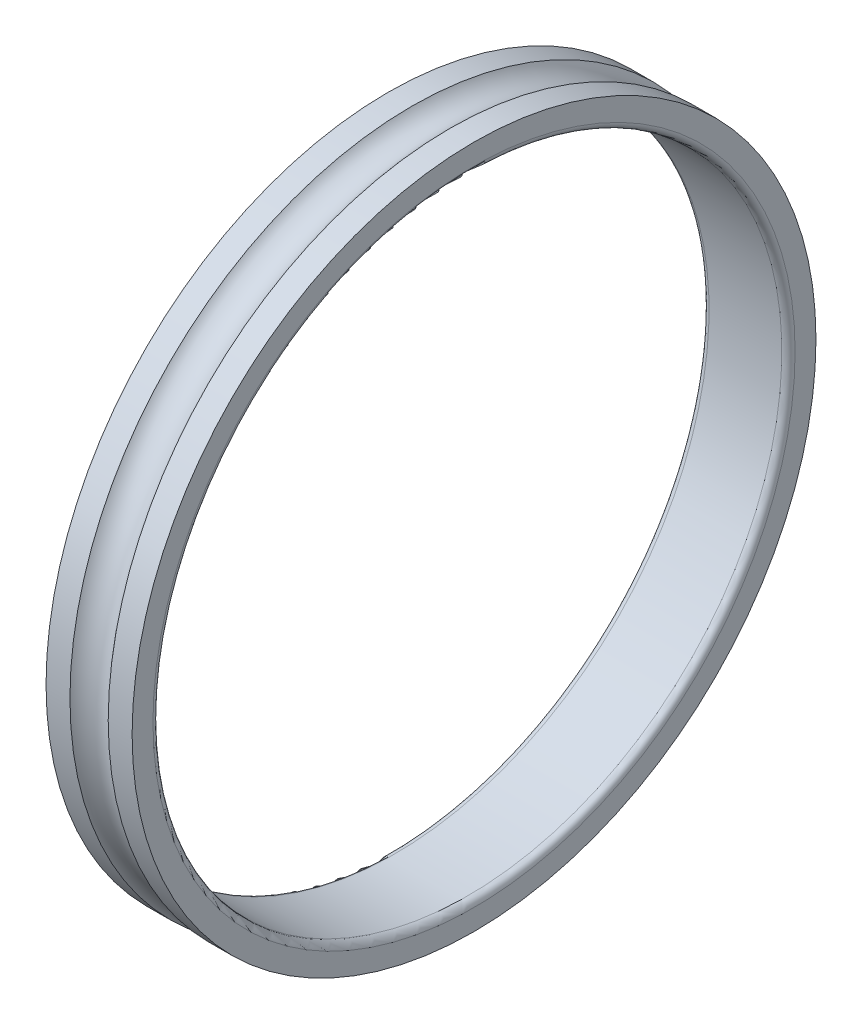
SolidWorks part; units mm, degrees
ref_plane "Piano frontale" through (0, 0, 0) normal (0, 0, 1) x (1, 0, 0)
ref_plane "Piano superiore" through (0, 0, 0) normal (0, 1, 0) x (1, 0, 0)
ref_plane "Piano destro" through (0, 0, 0) normal (1, 0, 0) x (0, 0, -1)
ref_plane "Piano1" through (0, 0, 0) normal (0, 0, 1) x (1, 0, 0)
sketch "Schizzo1" plane through (0, 0, 0) normal (0, 0, 1) x (1, 0, 0)
  line L0 (1, 47.5) -> (12, 47.5)
  line L1 (13, 48.5) -> (13, 51.65)
  line L2 (13, 51.65) -> (9.3895, 51.65)
  line L3 (3.6105, 51.65) -> (0, 51.65)
  line L4 (0, 51.65) -> (0, 48.5)
  line L5 (50, 0) -> (-50, 0) construction
  arc A0 (0, 48.5) -> (1, 47.5) centre (1, 48.5) ccw
  arc A1 (12, 47.5) -> (13, 48.5) centre (12, 48.5) ccw
  arc A2 (9.3895, 51.65) -> (3.6105, 51.65) centre (6.5, 53.75) cw
revolve "Rivoluzione1" add sketch "Schizzo1" angle 360 about L5
